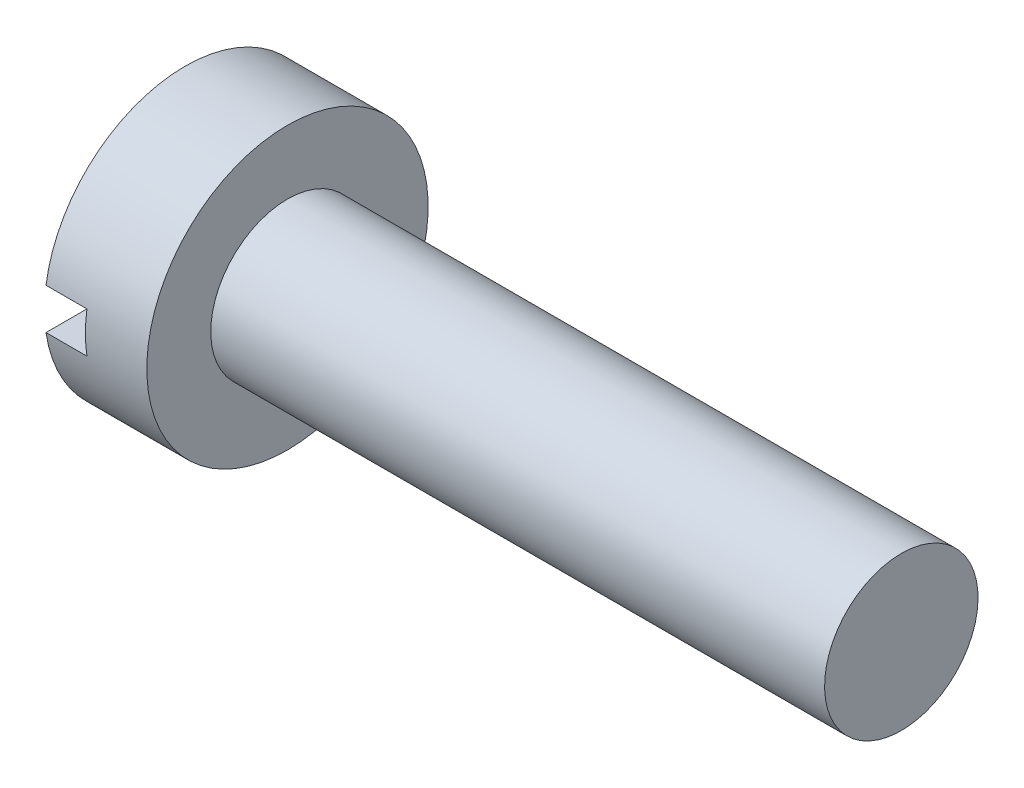
SolidWorks part; units mm, degrees
material "Plain Carbon Steel"
ref_plane "Front Plane" through (0, 0, 0) normal (0, 0, 1) x (1, 0, 0)
ref_plane "Top Plane" through (0, 0, 0) normal (0, 1, 0) x (1, 0, 0)
ref_plane "Right Plane" through (0, 0, 0) normal (1, 0, 0) x (0, 0, -1)
sketch "Sketch1" plane through (0, 0, 0) normal (0, 0, 1) x (1, 0, 0)
  line L0 (0, 0) -> (0, 2.75)
  line L1 (0, 2.75) -> (2, 2.75)
  line L2 (2, 2.75) -> (2, 1.5)
  line L3 (2, 1.5) -> (14, 1.5)
  line L4 (14, 1.5) -> (14, 0)
  line L5 (14, 0) -> (0, 0) construction
  line L6 (0, 0) -> (14, 0)
  dimension "D1" = 3
  dimension "D2" = 12
  dimension "D3" = 5.5
  dimension "D4" = 2
revolve "Revolve1" add sketch "Sketch1" angle 360 about L5
sketch "Sketch2" plane through (0, 0, 0) normal (-1, 0, 0) x (0, 0, 1)
  line L0 (2.75, 0) -> (-2.75, 0) construction
  line L1 (-2.75, 0.4) -> (2.75, 0.4)
  line L2 (-2.75, 0.4) -> (-2.75, -0.4)
  line L3 (-2.75, -0.4) -> (2.75, -0.4)
  line L4 (2.75, 0.4) -> (2.75, -0.4)
  circle A0 centre (0, 0) radius 2.75 construction
  dimension "D1" = 0.8
extrude "Cut-Extrude1" cut sketch "Sketch2" against normal blind 0.8
